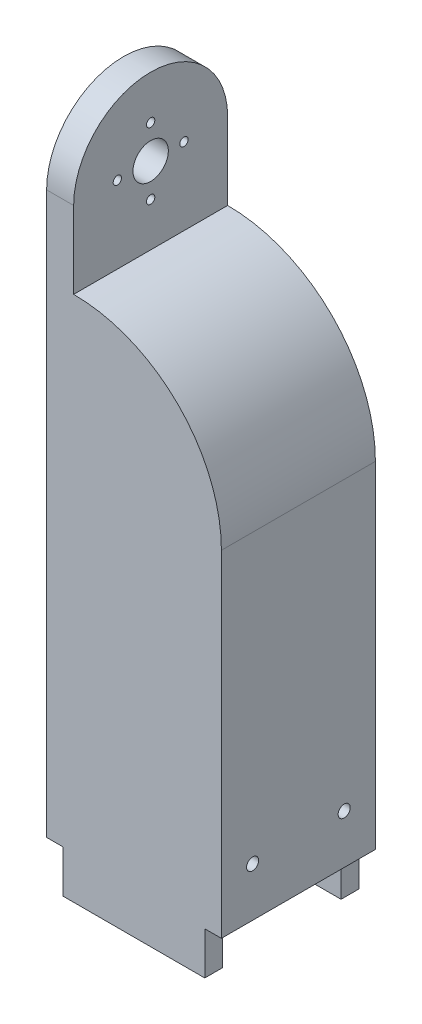
SolidWorks part; units mm, degrees
ref_plane "Front Plane" through (0, 0, 0) normal (0, 0, 1) x (1, 0, 0)
ref_plane "Top Plane" through (0, 0, 0) normal (0, 1, 0) x (1, 0, 0)
ref_plane "Right Plane" through (0, 0, 0) normal (1, 0, 0) x (0, 0, -1)
sketch "Sketch1" plane through (0, 0, 0) normal (0, 0, 1) x (1, 0, 0)
  line L1 (-25, 0) -> (25, 0)
  line L2 (-25, 0) -> (-25, -150)
  line L3 (-25, -150) -> (25, -150)
  line L4 (25, 0) -> (25, -150)
  dimension "D1" = 50
  dimension "D2" = 150
extrude "Boss-Extrude1" add sketch "Sketch1" against normal blind 55
sketch "Sketch2" plane through (25, 0, 0) normal (1, 0, 0) x (0, 0, -1)
  line L0 (55, 0) -> (0, 0) construction
  line L1 (0, -150) -> (0, 0) construction
  circle A0 centre (27.5, -25) radius 10.25
  dimension "D1" = 25
  dimension "D2" = 27.5
extrude "Cut-Extrude1" cut sketch "Sketch2" against normal blind 45 and the other way through all
sketch "Sketch7" plane through (-20, 0, 0) normal (1, 0, 0) x (0, 0, -1)
  line L0 (27.5, -17) -> (27.5, -33) construction
  circle A0 centre (27.5, -25) radius 8
  circle A1 centre (27.5, -17) radius 1
  circle A2 centre (35.5, -25) radius 1
  circle A3 centre (27.5, -33) radius 1
  circle A4 centre (19.5, -25) radius 1
  circle A5 centre (27.5, -25) radius 4.25
  point P14 (27.5, -25)
  dimension "D1" = 16
  dimension "D2" = 2
  dimension "D4" = 8.5
  dimension "D3" = 4
extrude "Cut-Extrude3" cut sketch "Sketch7" against normal blind 10 contours L0 A0 A1 | A0 A1 | A0 L0 A1 | A0 A4 | A0 A4 | L0 A3 A0 | A3 L0 A0 | A0 A3 | A0 A2 | A0 A2 | A5 L0 | L0 A5
sketch "Sketch8" plane through (25, 0, 0) normal (1, 0, 0) x (0, 0, -1)
  line L1 (55, -150) -> (55, 0) construction
  line L3 (0, -150) -> (55, -150)
  line L4 (0, -150) -> (0, -205)
  line L5 (0, -205) -> (55, -205)
  line L6 (55, -150) -> (55, -205)
  circle A1 centre (27.5, -180) radius 10.25
  circle A3 centre (27.5, -25) radius 10.25 construction
  dimension "D1" = 27.5
  dimension "D2" = 155
  dimension "D3" = 25
extrude "Boss-Extrude2" add sketch "Sketch8" against normal blind 50
sketch "Sketch10" plane through (0, 0, 0) normal (0, 0, 1) x (1, 0, 0)
  line L0 (-25, -205) -> (25, -205) construction
  line L5 (17, -205) -> (-17, -205)
  line L6 (17, -205) -> (17, -144.75)
  line L8 (-17, -205) -> (-17, -144.75)
  line L9 (-25, 0) -> (-25, -205) construction
  line L10 (-25, -180) -> (25, -180)
  line L13 (25, -169.75) -> (-25, -169.75)
  line L14 (25, -169.75) -> (25, -190.25)
  line L15 (25, -190.25) -> (-25, -190.25)
  line L16 (-25, -169.75) -> (-25, -190.25)
  line L17 (25, -205) -> (25, 0) construction
  line L18 (0, -180) -> (17, -180)
  line L19 (0, -180) -> (0, -191.25)
  line L20 (0, -191.25) -> (17, -191.25)
  line L21 (17, -180) -> (17, -191.25)
  line L22 (17, -191.25) -> (-17, -191.25)
  line L23 (17, -191.25) -> (17, -169.75)
  line L24 (17, -169.75) -> (-17, -169.75)
  line L25 (-17, -191.25) -> (-17, -169.75)
  line L26 (17, -191.25) -> (-17, -191.25)
  line L27 (17, -191.25) -> (17, -144.75)
  line L28 (17, -144.75) -> (-17, -144.75)
  line L29 (-17, -191.25) -> (-17, -144.75)
  line L30 (-25, -169.75) -> (-17, -169.75)
  line L31 (-25, -169.75) -> (-25, -205)
  line L32 (-25, -205) -> (-17, -205)
  line L33 (-17, -169.75) -> (-17, -205)
  line L34 (25, -169.75) -> (17, -169.75)
  line L35 (25, -169.75) -> (25, -205)
  line L36 (25, -205) -> (17, -205)
  line L37 (17, -169.75) -> (17, -205)
  line L38 (-25, -169.75) -> (25, -169.75)
  line L39 (-25, -169.75) -> (-25, -164.75)
  line L40 (-25, -164.75) -> (25, -164.75)
  line L41 (25, -169.75) -> (25, -164.75)
  line M7 (-25, 0) -> (-25, -205)
  line M8 (-25, -205) -> (25, -205)
  line M9 (25, -205) -> (25, 0)
  dimension "D1" = 8
  dimension "D2" = 8
  dimension "D3" = 11.25
  dimension "D4" = 46.5
  dimension "D5" = 60.25
  dimension "D6" = 5
extrude "Cut-Extrude4" cut sketch "Sketch10" against normal through all contours L20 L22 L8 L6 M8 | L8 L15 M7 M8 | L15 L6 M9 M8 | L15 L8 L10 M7 | L8 L13 L10 M7 | L13 L6 L10 M9 | L15 L10 L6 M9 | L19 L10 L8 L15 | L10 L19 L15 L6 | L6 L13 L8 L10 | L22 L19 L15 L8 | L19 L20 L6 L15 | L29 L40 L27 L28 | L40 L8 L13 L6
sketch "Sketch11" plane through (0, -144.75, 0) normal (0, -1, 0) x (1, 0, 0)
  line L0 (17, -55) -> (17, 0) construction
  line L1 (-17, 0) -> (17, 0)
  line L2 (-17, 0) -> (-17, -13.25)
  line L3 (-17, -13.25) -> (17, -13.25)
  line L4 (17, 0) -> (17, -13.25)
  line L5 (25, -27.5) -> (-30.9131, -27.5) construction
  line L6 (25, -55) -> (25, 0) construction
  line L7 (17, -55) -> (17, -41.75)
  line L8 (-17, -41.75) -> (17, -41.75)
  line L9 (-17, -55) -> (-17, -41.75)
  line L10 (-17, -55) -> (17, -55)
  dimension "D1" = 14.25
extrude "Boss-Extrude4" add sketch "Sketch11" along normal blind 25
sketch "Sketch13" plane through (25, 0, 0) normal (1, 0, 0) x (0, 0, -1)
  line L0 (0, -169.75) -> (0, 0) construction
  line L1 (55, -169.75) -> (0, -169.75)
  line L2 (55, -169.75) -> (55, -159.75)
  line L3 (55, -159.75) -> (0, -159.75)
  line L4 (0, -169.75) -> (0, -159.75)
  dimension "D1" = 10
extrude "Cut-Extrude5" cut sketch "Sketch13" against normal blind 8
ref_plane "Plane2" through (0, 0, 0) normal (1, 0, 0) x (0, 0, -1)
mirror "Mirror2" about plane through (0, 0, 0) normal (1, 0, 0) of "Cut-Extrude5"
sketch "Sketch14" plane through (25, 0, 0) normal (1, 0, 0) x (0, 0, -1)
  line L0 (55, -159.75) -> (0, -159.75) construction
  line L1 (0, -159.75) -> (0, 0) construction
  circle A1 centre (16.5, -148) radius 5.0302
  circle A2 centre (38.5, -148) radius 5.0302
  dimension "D1" = 16.5
  dimension "D2" = 2
  dimension "D3" = 11.75
extrude "Cut-Extrude6" cut sketch "Sketch14" against normal blind 8
mirror "Mirror3" about plane through (0, 0, 0) normal (1, 0, 0) of "Cut-Extrude6"
sketch "Sketch15" plane through (0, 0, 0) normal (0, 0, 1) x (1, 0, 0)
  line L0 (-25, 0) -> (25, 0)
  line L1 (25, 0) -> (0, 0)
  line L3 (-17, -169.75) -> (17, -169.75)
  line L4 (-17, -169.75) -> (-17, -170)
  line L5 (-17, -170) -> (17, -170)
  line L6 (17, -169.75) -> (17, -170)
  line M5 (-17, -169.75) -> (17, -169.75)
  dimension "D1" = 0.25
extrude "Boss-Extrude5" add sketch "Sketch15" against normal blind 13.25 contours L6 L4 L5 M5
ref_plane "Plane3" through (0, 0, -27.5) normal (0, 0, 1) x (1, 0, 0)
mirror "Mirror4" about plane through (0, 0, -27.5) normal (0, 0, 1) of "Boss-Extrude5"
sketch "Sketch16" plane through (0, 0, 0) normal (0, 0, 1) x (1, 0, 0)
  line L7 (-20, -14.75) -> (-18.5, -14.75)
  line L8 (-20, -14.75) -> (-20, -35.25)
  line L9 (-20, -35.25) -> (-18.5, -35.25)
  line L10 (-18.5, -14.75) -> (-18.5, -35.25)
  line L11 (25, 0) -> (-18.5, 0)
  line L12 (25, 0) -> (25, -43.5)
  line L13 (25, -43.5) -> (-18.5, -43.5)
  line L14 (-18.5, 0) -> (-18.5, -43.5)
  line M12 (25, -159.75) -> (25, 0)
  line M13 (25, 0) -> (-25, 0)
  dimension "D1" = 1.5
  dimension "D2" = 43.5
  dimension "D3" = 43.5
extrude "Cut-Extrude7" cut sketch "Sketch16" against normal through all contours L14 L10 L13 M13 M12
sketch "Sketch19" plane through (-20, 0, 0) normal (1, 0, 0) x (0, 0, -1)
  circle A0 centre (27.5, -25) radius 4.25
  circle A1 centre (35.5, -25) radius 1
  circle A2 centre (27.5, -33) radius 1
  circle A3 centre (19.5, -25) radius 1
  circle A4 centre (27.5, -17) radius 1
  point P15 (27.5, -25)
  circle M5 centre (27.5, -25) radius 4.25
  circle M6 centre (27.5, -17) radius 1
  circle M7 centre (35.5, -25) radius 1
  circle M8 centre (27.5, -33) radius 1
  circle M9 centre (19.5, -25) radius 1
  circle M10 centre (27.5, -25) radius 10.25
  dimension "D1" = 4
extrude "Boss-Extrude6" add sketch "Sketch19" along normal blind 1.5 contours M10 M6 M8 M9 M7 M5
sketch "Sketch20" plane through (-18.5, 0, 0) normal (1, 0, 0) x (0, 0, -1)
  line L0 (0, -43.5) -> (9, -43.5)
  line L1 (9, -25) -> (9, -43.5)
  line L2 (9, -43.5) -> (0, -43.5)
  line L3 (46, -25) -> (46, -43.5)
  line L4 (46, -43.5) -> (55, -43.5)
  line L5 (46, -43.5) -> (55, -43.5)
  line L7 (9, -43.5) -> (0, -43.5)
  line L8 (9, -43.5) -> (9, -25)
  line L12 (9, -25) -> (9, -43.5)
  line L13 (9, -43.5) -> (0, -43.5)
  line L15 (0, 0) -> (55, 0)
  line L16 (0, 0) -> (0, -43.5)
  line L17 (0, -43.5) -> (55, -43.5)
  line L18 (55, 0) -> (55, -43.5)
  circle A0 centre (27.5, -25) radius 18.5
  line M6 (0, 0) -> (0, -43.5)
  line M7 (0, -43.5) -> (55, -43.5)
  line M8 (55, -43.5) -> (55, 0)
  line M9 (55, 0) -> (0, 0)
extrude "Cut-Extrude8" cut sketch "Sketch20" against normal through all contours A0 L3 L1 M7 M8 M9 M6
sketch "Sketch21" plane through (25, 0, 0) normal (1, 0, 0) x (0, 0, -1)
  circle A0 centre (16.5, -148) radius 5.0302
  circle A1 centre (16.5, -148) radius 4.5
  circle A2 centre (38.5, -148) radius 4.5
  circle A3 centre (38.5, -148) radius 5.0302
  dimension "D1" = 2
extrude "Boss-Extrude7" add sketch "Sketch21" against normal blind 8
mirror "Mirror5" about plane through (0, 0, 0) normal (1, 0, 0) of "Boss-Extrude7"
sketch "Sketch24" plane through (0, 0, 0) normal (0, 0, 1) x (1, 0, 0)
  line L1 (-25, -159.75) -> (-21, -159.75)
  line L2 (-25, -159.75) -> (-25, -129.75)
  line L3 (-25, -129.75) -> (-21, -129.75)
  line L4 (-21, -159.75) -> (-21, -129.75)
  line L5 (25, -159.75) -> (21, -159.75)
  line L6 (25, -159.75) -> (25, -129.75)
  line L7 (25, -129.75) -> (21, -129.75)
  line L8 (21, -159.75) -> (21, -129.75)
  dimension "D1" = 30
  dimension "D2" = 30
  dimension "D3" = 4
  dimension "D4" = 4
extrude "Cut-Extrude10" cut sketch "Sketch24" against normal through all
sketch "Sketch25" plane through (25, 0, 0) normal (1, 0, 0) x (0, 0, -1)
  line L1 (0, -43.5) -> (55, -43.5)
  line L2 (0, -43.5) -> (0, -129.75)
  line L3 (0, -129.75) -> (55, -129.75)
  line L4 (55, -43.5) -> (55, -129.75)
extrude "Cut-Extrude11" cut sketch "Sketch25" against normal blind 4
sketch "Sketch26" plane through (-18.5, 0, 0) normal (1, 0, 0) x (0, 0, -1)
  line L1 (46, -43.5) -> (9, -43.5)
  line L2 (46, -43.5) -> (46, -25)
  line L3 (46, -25) -> (9, -25)
  line L4 (9, -43.5) -> (9, -25)
  circle A0 centre (27.5, -25) radius 18.5
  circle A1 centre (27.5, -25) radius 4.25
  circle A2 centre (27.5, -33) radius 1
  circle A3 centre (35.5, -25) radius 1
  circle A4 centre (27.5, -17) radius 1
  circle A5 centre (19.5, -25) radius 1
  circle M1 centre (27.5, -25) radius 4.25
  circle M2 centre (35.5, -25) radius 1
  circle M3 centre (19.5, -25) radius 1
  circle M4 centre (27.5, -33) radius 1
  circle M5 centre (27.5, -17) radius 1
  line M6 (9, -25) -> (9, -43.5)
  line M7 (9, -43.5) -> (46, -43.5)
  line M8 (46, -43.5) -> (46, -25)
  arc M9 (46, -25) -> (9, -25) centre (27.5, -25) ccw
extrude "Boss-Extrude8" add sketch "Sketch26" along normal blind 4 contours A0 M6 M7 | A0 L1 M8 | L3 A0 M2 M1 M3 M4 | L3 M9 M3 M1 M2 M5
sketch "Sketch27" plane through (0, 0, 0) normal (0, 0, 1) x (1, 0, 0)
  line L1 (-21, -129.75) -> (-25, -129.75)
  line L2 (-21, -129.75) -> (-21, -6.5)
  line L3 (-21, -6.5) -> (-25, -6.5)
  line L4 (-25, -129.75) -> (-25, -6.5)
extrude "Cut-Extrude12" cut sketch "Sketch27" against normal through all
sketch "Sketch28" plane through (0, 0, 0) normal (0, 0, 1) x (1, 0, 0)
  line L1 (-14.5, -43.5) -> (-21, -43.5)
  line L2 (21, -79) -> (21, -159.75)
  line L3 (21, -159.75) -> (-21, -159.75)
  line L4 (-21, -43.5) -> (-21, -159.75)
  line L5 (21, -43.5) -> (-21, -43.5)
  line L6 (21, -43.5) -> (21, -159.75)
  line L7 (21, -159.75) -> (-21, -159.75)
  line L8 (-21, -43.5) -> (-21, -159.75)
  arc A0 (21, -79) -> (-14.5, -43.5) centre (-14.5, -79) ccw
  point P8 (21, -43.5)
  line M2 (21, -43.5) -> (-21, -43.5)
  line M9 (21, -159.75) -> (21, -43.5)
  dimension "D1" = 35.5
extrude "Cut-Extrude13" cut sketch "Sketch28" against normal through all contours A0 M9 M2
sketch "Sketch29" plane through (0, -170, 0) normal (0, -1, 0) x (1, 0, 0)
  line L5 (-21, -55) -> (-21, 0) construction
  line L6 (21, -55) -> (-21, -55)
  line L7 (21, -55) -> (21, -46)
  line L8 (21, -46) -> (-21, -46)
  line L9 (-21, -55) -> (-21, -46)
  line L10 (21, -55) -> (21, 0) construction
  line L11 (-21, 0) -> (21, 0)
  line L12 (-21, 0) -> (-21, -9)
  line L13 (-21, -9) -> (21, -9)
  line L14 (21, 0) -> (21, -9)
  dimension "D1" = 9
  dimension "D2" = 9
extrude "Cut-Extrude15" cut sketch "Sketch29" against normal through all
sketch "Sketch30" plane through (21, 0, 0) normal (1, 0, 0) x (0, 0, -1)
  circle A0 centre (16.5, -148) radius 4.5
  circle A1 centre (38.5, -148) radius 4.5
  circle A2 centre (16.5, -148) radius 1.45
  circle A3 centre (38.5, -148) radius 1.45
extrude "Boss-Extrude9" add sketch "Sketch30" against normal blind 4
mirror "Mirror6" about plane through (0, 0, 0) normal (1, 0, 0) of "Boss-Extrude9"
